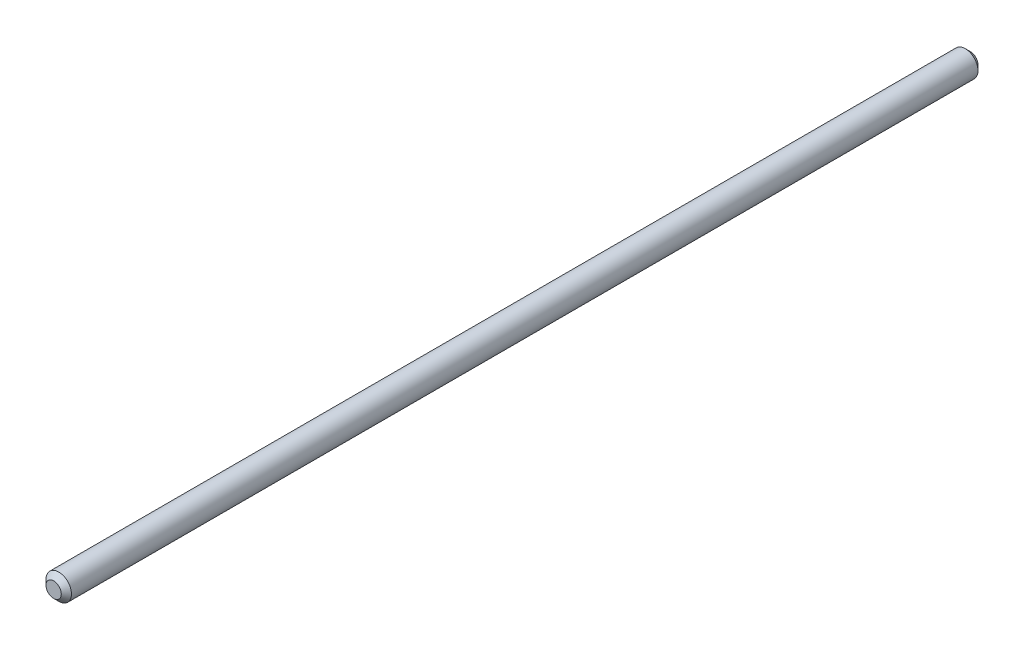
SolidWorks part; units mm, degrees
ref_plane "Front Plane" through (0, 0, 0) normal (0, 0, 1) x (1, 0, 0)
ref_plane "Top Plane" through (0, 0, 0) normal (0, 1, 0) x (1, 0, 0)
ref_plane "Right Plane" through (0, 0, 0) normal (1, 0, 0) x (0, 0, -1)
sketch "Sketch1" plane through (0, 0, 0) normal (0, 0, 1) x (1, 0, 0)
  circle A0 centre (0, 0) radius 1.25
  dimension "D1" = 2.5
extrude "Boss-Extrude1" add sketch "Sketch1" along normal blind 90
chamfer "Chamfer1" distance 0.5 angle 45 1 edges at (1.25, 0, 0)
chamfer "Chamfer2" distance 0.5 angle 45 1 edges at (1.25, 0, 90)
